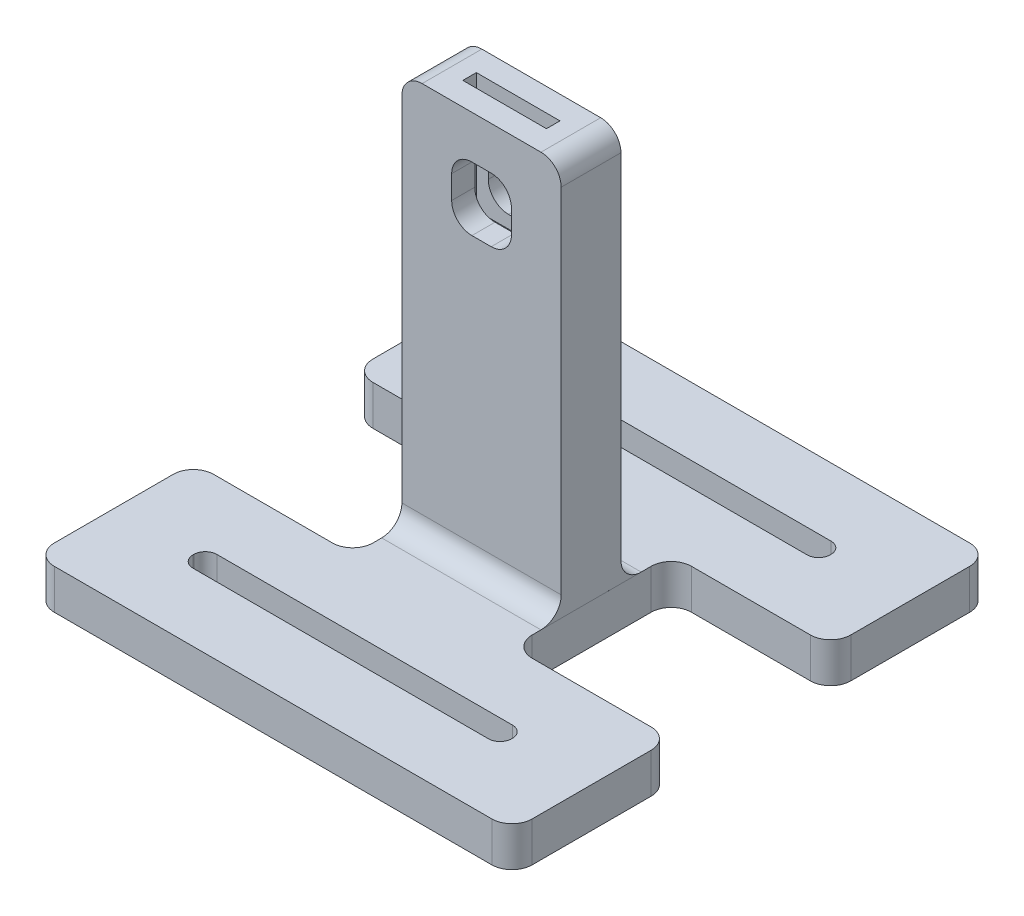
SolidWorks part; units mm, degrees
ref_plane "Front Plane" through (0, 0, 0) normal (0, 0, 1) x (1, 0, 0)
ref_plane "Top Plane" through (0, 0, 0) normal (0, 1, 0) x (1, 0, 0)
ref_plane "Right Plane" through (0, 0, 0) normal (1, 0, 0) x (0, 0, -1)
sketch "Sketch1" plane through (0, 0, 0) normal (0, 1, 0) x (1, 0, 0)
  line L0 (0.0004, -29.9264) -> (0.0004, 30.0736) construction
  line L1 (-29.9996, -29.9264) -> (30.0004, -29.9264)
  line L2 (-29.9996, -29.9264) -> (-29.9996, -9.9264)
  line L3 (-29.9996, 30.0736) -> (30.0004, 30.0736)
  line L4 (30.0004, -29.9264) -> (30.0004, -9.9264)
  line L5 (10.0004, -9.9264) -> (30.0004, -9.9264)
  line L6 (-9.9996, -9.9264) -> (-29.9996, -9.9264)
  line L7 (10.0004, 10.0736) -> (-9.9996, 10.0736) construction
  line L8 (10.0004, 10.0736) -> (10.0004, -9.9264)
  line L9 (10.0004, -9.9264) -> (-9.9996, -9.9264) construction
  line L10 (-9.9996, 10.0736) -> (-9.9996, -9.9264)
  line L11 (-29.9996, 30.0736) -> (-29.9996, 10.0736)
  line L12 (30.0004, 30.0736) -> (30.0004, 10.0736)
  line L13 (10.0004, 10.0736) -> (-9.9996, -9.9264) construction
  line L14 (10.0004, -9.9264) -> (-9.9996, 10.0736) construction
  line L15 (30.0004, 10.0736) -> (10.0004, 10.0736)
  line L16 (-9.9996, 10.0736) -> (-29.9996, 10.0736)
  point P9 (0.0004, 0.0736)
  dimension "D1" = 60
  dimension "D2" = 60
  dimension "D3" = 20
  dimension "D5" = 20
  dimension "D6" = 20
extrude "Boss-Extrude1" add sketch "Sketch1" along normal blind 5
sketch "Sketch2" plane through (0, 5, 0) normal (0, 1, 0) x (1, 0, 0)
  line L0 (-29.9996, 20.0736) -> (30.0004, 20.0736) construction
  line L1 (-29.9996, 30.0736) -> (-29.9996, 10.0736) construction
  line L2 (30.0004, 30.0736) -> (30.0004, 10.0736) construction
  line L8 (-29.9996, -19.9264) -> (30.0004, -19.9264) construction
  line L9 (-29.9996, -29.9264) -> (-29.9996, -9.9264) construction
  line L10 (30.0004, -29.9264) -> (30.0004, -9.9264) construction
  line L17 (-18.5492, 18.5736) -> (18.55, 18.5736)
  line L18 (-19.9992, 20.0236) -> (-19.9992, 20.1236)
  line L19 (-18.5492, 21.5736) -> (18.55, 21.5736)
  line L20 (20, 20.0236) -> (20, 20.1236)
  line L21 (-19.9992, 18.5736) -> (20, 21.5736) construction
  line L22 (-19.9992, 21.5736) -> (20, 18.5736) construction
  line L23 (-18.5496, -21.4264) -> (18.5504, -21.4264)
  line L24 (-19.9996, -19.9764) -> (-19.9996, -19.8764)
  line L25 (-18.5496, -18.4264) -> (18.5504, -18.4264)
  line L26 (20.0004, -19.9764) -> (20.0004, -19.8764)
  line L27 (-19.9996, -21.4264) -> (20.0004, -18.4264) construction
  line L28 (-19.9996, -18.4264) -> (20.0004, -21.4264) construction
  arc A0 (-18.5496, -21.4264) -> (-19.9996, -19.9764) centre (-18.5496, -19.9764) cw
  arc A1 (-19.9996, -19.8764) -> (-18.5496, -18.4264) centre (-18.5496, -19.8764) cw
  arc A2 (18.5504, -21.4264) -> (20.0004, -19.9764) centre (18.5504, -19.9764) ccw
  arc A3 (18.5504, -18.4264) -> (20.0004, -19.8764) centre (18.5504, -19.8764) cw
  arc A4 (18.55, 18.5736) -> (20, 20.0236) centre (18.55, 20.0236) ccw
  arc A5 (-18.5492, 18.5736) -> (-19.9992, 20.0236) centre (-18.5492, 20.0236) cw
  arc A6 (18.55, 21.5736) -> (20, 20.1236) centre (18.55, 20.1236) cw
  arc A7 (-19.9992, 20.1236) -> (-18.5492, 21.5736) centre (-18.5492, 20.1236) cw
  point P32 (0.0004, 20.0736)
  point P37 (0.0004, -19.9264)
  dimension "D3" = 1.45
  dimension "D1" = 3
  dimension "D2" = 3
  dimension "D4" = 10
extrude "Cut-Extrude1" cut sketch "Sketch2" against normal through all
fillet "Fillet1" radius 2.54 12 edges at (-29.9996, 2.5, -30.0736) (-29.9996, 2.5, 29.9264) (30.0004, 2.5, 29.9264) (30.0004, 2.5, -30.0736) (10.0004, 2.5, -10.0736) (30.0004, 2.5, -10.0736) (-29.9996, 2.5, -10.0736) (-9.9996, 2.5, -10.0736) (-29.9996, 2.5, 9.9264) (-9.9996, 2.5, 9.9264) (10.0004, 2.5, 9.9264) (30.0004, 2.5, 9.9264)
sketch "Sketch3" plane through (0, 5, 0) normal (0, 1, 0) x (1, 0, 0)
  line L1 (-10, 3.75) -> (10, 3.75)
  line L2 (-10, 3.75) -> (-10, -3.75)
  line L3 (-10, -3.75) -> (10, -3.75)
  line L4 (10, 3.75) -> (10, -3.75)
  line L5 (-10, 3.75) -> (10, -3.75) construction
  line L6 (-10, -3.75) -> (10, 3.75) construction
  point P0 (0, 0)
  dimension "D1" = 7.5
  dimension "D2" = 20
extrude "Boss-Extrude2" add sketch "Sketch3" along normal blind 34.4
sketch "Sketch4" plane through (0, 39.4, 0) normal (0, 1, 0) x (1, 0, 0)
  line L0 (-10, 3.75) -> (-10, -3.75) construction
  line L1 (10, 0.85) -> (-10, 0.85)
  line L2 (10, 0.85) -> (10, -0.85)
  line L3 (10, -0.85) -> (-10, -0.85)
  line L4 (-10, 0.85) -> (-10, -0.85)
  line L5 (10, 0.85) -> (-10, -0.85) construction
  line L6 (10, -0.85) -> (-10, 0.85) construction
  line L8 (5.25, 0.85) -> (-5.25, 0.85)
  line L9 (5.25, 0.85) -> (5.25, -0.85)
  line L10 (5.25, -0.85) -> (-5.25, -0.85)
  line L11 (-5.25, 0.85) -> (-5.25, -0.85)
  line L12 (5.25, 0.85) -> (-5.25, -0.85) construction
  line L13 (5.25, -0.85) -> (-5.25, 0.85) construction
  point P0 (0, 0)
  point P8 (0, 0)
  point P13 (5.25, 0)
  line M3 (10, -3.75) -> (10, 3.75)
  line M4 (10, 3.75) -> (-10, 3.75)
  line M5 (-10, 3.75) -> (-10, -3.75)
  line M6 (-10, -3.75) -> (10, -3.75)
  dimension "D1" = 1.7
  dimension "D2" = 10.5
extrude "Boss-Extrude3" add sketch "Sketch4" along normal blind 15 contours L3 M3 M5 M6 | L1 L9 L3 M3 | L1 M3 M4 M5 | L11 L1 L3 M5
sketch "Sketch5" plane through (0, 0, -3.75) normal (0, 0, -1) x (-1, 0, 0)
  line L0 (-10, 39.4) -> (10, 39.4) construction
  line L1 (-10, 54.4) -> (-10, 5) construction
  line L2 (10, 54.4) -> (10, 5) construction
  line L3 (-10, 54.4) -> (10, 54.4) construction
  line L4 (-10, 50.6) -> (10, 50.6) construction
  line L5 (0, 50.6) -> (0, 39.4) construction
  line L7 (-1.21, 41) -> (1.21, 41)
  line L8 (-3.75, 43.54) -> (-3.75, 46.46)
  line L9 (-1.21, 49) -> (1.21, 49)
  line L10 (3.75, 43.54) -> (3.75, 46.46)
  line L11 (-3.75, 41) -> (3.75, 49) construction
  line L12 (-3.75, 49) -> (3.75, 41) construction
  arc A0 (-1.21, 41) -> (-3.75, 43.54) centre (-1.21, 43.54) cw
  arc A1 (1.21, 41) -> (3.75, 43.54) centre (1.21, 43.54) ccw
  arc A2 (1.21, 49) -> (3.75, 46.46) centre (1.21, 46.46) cw
  arc A3 (-3.75, 46.46) -> (-1.21, 49) centre (-1.21, 46.46) cw
  point P12 (0, 45)
  dimension "D5" = 2.54
  dimension "D1" = 15
  dimension "D2" = 11.2
  dimension "D3" = 8
  dimension "D4" = 7.5
extrude "Cut-Extrude2" cut sketch "Sketch5" against normal through all
fillet "Fillet2" radius 2.54 4 edges at (0.0002, 5, -3.75) (0.0002, 5, 3.75) (-10, 54.4, 0) (10, 54.4, 0)
